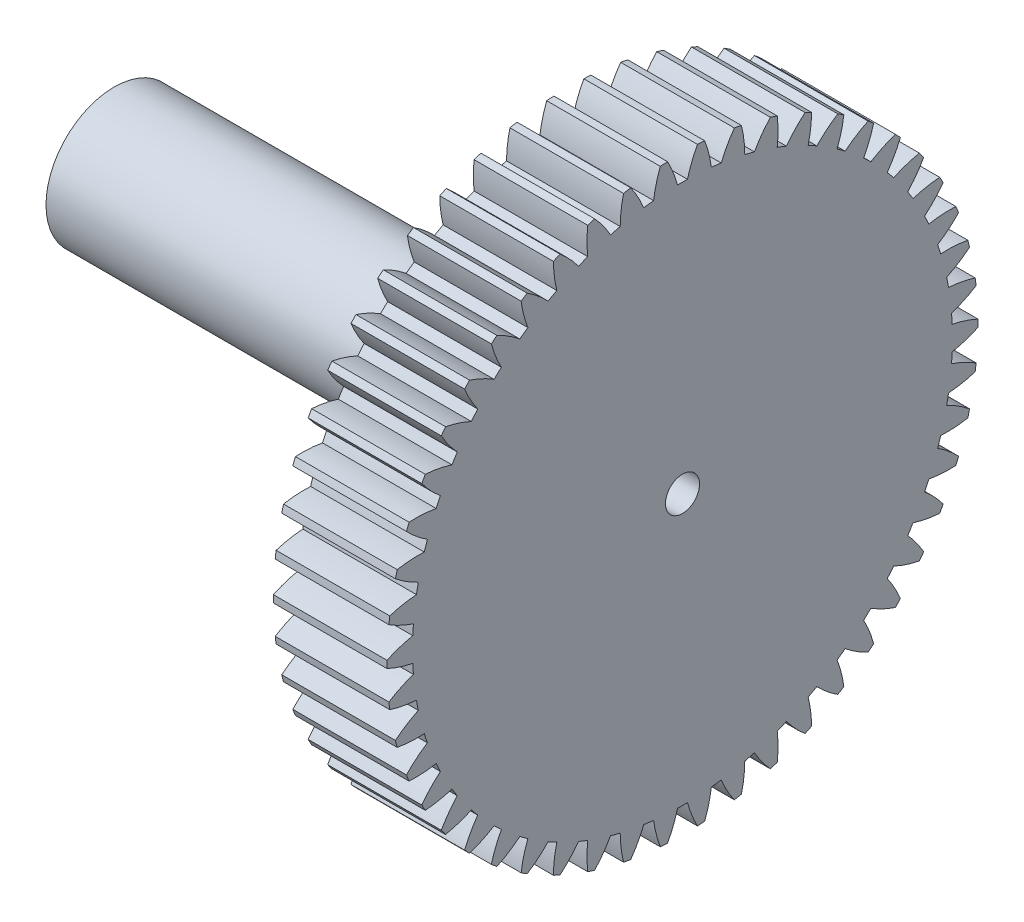
SolidWorks part; units mm, degrees
ref_plane "Plane1" through (0, 0, 0) normal (0, 0, 1) x (1, 0, 0)
ref_plane "Plane2" through (0, 0, 0) normal (0, 1, 0) x (1, 0, 0)
ref_plane "Plane3" through (0, 0, 0) normal (1, 0, 0) x (0, 0, -1)
sketch "HoldingSke" plane through (0, 0, 0) normal (0, 1, 0) x (1, 0, 0)
  line L0 (0, 0) -> (0.6428, -0.766)
  line L1 (-15, 0) -> (100, 0) construction
  line L2 (0, 0) -> (-2.1039, 2.3779)
  line L3 (0, 0) -> (-11.863, 4.5341)
  line L4 (0, 0) -> (5.5511, 6.6156)
  line L5 (0, 0) -> (-46.8476, -17.4728)
  line L6 (0, 0) -> (-8.2896, -5.593)
  line L7 (-2.1039, 2.3779) -> (8.6586, 51.2059)
  line L8 (-76.2, 54.61) -> (-75.7, 54.61)
  line L9 (-71.009, 38.7566) -> (-53.1078, 45.2721)
  line L10 (-76.2, 71.12) -> (104.1128, 71.12)
  line L11 (0, 0) -> (-10, 0)
  line L12 (-76.2, 101.6) -> (-76.162, 101.6)
  line L13 (24.9733, 27.94) -> (52.9518, 28.4284)
  line L14 (24.9733, 27.94) -> (24.9743, 27.94)
  line L15 (24.9733, 27.94) -> (100.4006, 29.5858)
  line L16 (-63.627, -1) -> (-12.827, -1)
  circle A0 centre (0, 0) radius 1.5
  circle A1 centre (0, 0) radius 6
  circle A2 centre (0, 0) radius 6
  circle A3 centre (0, 0) radius 1.5
  dimension "MHD" = 12
  dimension "Hub_dia" = 12
  dimension "Bore" = 3
  dimension "MBD" = 3
  dimension "Num_teeth" = 50
  dimension "Pitch" = 1
  dimension "Overall_len" = 50
  dimension "Show_teeth" = 50
  dimension "Thickness" = 10
  dimension "OAL" = 50.0001
  dimension "T_dim" = 0.5
  dimension "Ap" = 20
  dimension "H" = 19.05
  dimension "Pitch_radius" = 180.3128
  dimension "Width" = 10
  dimension "Backlash" = 0.038
  dimension "Addendum_fac" = 1
  dimension "Dedendum_fac" = 1.25
  dimension "Clearance_fac" = 0.25
  dimension "Dedendum_add" = 0.001
  dimension "Module" = 1
sketch "BasProSke" plane through (0, 0, 0) normal (0, 1, 0) x (1, 0, 0)
  line L0 (-10, 0) -> (60, 0) construction
  line L1 (0, 0) -> (0, 26)
  line L2 (0, 0) -> (10, 0)
  line L3 (10, 0) -> (10, 26)
  line L4 (10, 26) -> (0, 26)
  dimension "Thickness" = 10
  dimension "Diameter" = 52
revolve "Base-Revolve" add sketch "BasProSke" angle 360 about L0
sketch "TooCutSke" plane through (0, 0, 0) normal (1, 0, 0) x (0, 0, -1)
  line L1 (0, 0) -> (0, 107) construction
  line L2 (0, 0) -> (-0.8518, 24.9855) construction
  line L3 (0, 0) -> (-3.1382, 49.8807) construction
  line L4 (-0.8518, 24.9855) -> (-1.5691, 24.9404) construction
  arc A0 (0.4377, 23.745) -> (-0.4377, 23.745) centre (0, 0) ccw
  arc A1 (1.3294, 25.9914) -> (-1.3294, 25.9914) centre (0, 0) ccw
  circle A2 centre (0, 0) radius 25 construction
  circle A3 centre (0, 0) radius 23.4923 construction
  arc A4 (-0.4377, 23.745) -> (-1.3294, 25.9914) centre (-10.1099, 21.2056) ccw
  arc A5 (1.3294, 25.9914) -> (0.4377, 23.745) centre (10.1099, 21.2056) ccw
  dimension "Root_dia" = 47.498
  dimension "Overcut_dia" = 52.0508
  dimension "Pitch_dia" = 50
  dimension "Base_dia" = 46.9846
  dimension "Flank_rad" = 10
  dimension "Half_ang" = 3.6
  dimension "Half_CT" = 0.7188
extrude "ToothCut" cut sketch "TooCutSke" along normal through all
fillet "Breaks" [suppressed] radius 0.02
fillet "RootFillets" [suppressed] radius 0.251
pattern_circular "TeethCuts" count 50 every 7.2 about axis through (-10, 0, 0) along (1, 0, 0) of "ToothCut", "RootFillets", "Breaks"
sketch "HubNeaOneSke" plane through (0, 0, 0) normal (-1, 0, 0) x (0, 0, 1)
  circle A0 centre (0, 0) radius 6
  dimension "Diameter" = 12
extrude "HubNearOne" add sketch "HubNeaOneSke" along normal blind 40.0001
sketch "HubNeaBotSke" plane through (0, 0, 0) normal (-1, 0, 0) x (0, 0, 1)
  circle A0 centre (0, 0) radius 6
  dimension "Diameter" = 12
extrude "HubNearBoth" [suppressed] add sketch "HubNeaBotSke" along normal blind 20
ref_plane "FarPln" through (10, 0, 0) normal (1, 0, 0) x (0, 0, -1)
sketch "HubFarSke" plane through (10, 0, 0) normal (1, 0, 0) x (0, 0, -1)
  circle A0 centre (0, 0) radius 6
  dimension "Diameter" = 12
extrude "HubFar" [suppressed] add sketch "HubFarSke" along normal blind 20
sketch "BorSke" plane through (0, 0, 0) normal (1, 0, 0) x (0, 0, -1)
  circle A0 centre (0, 0) radius 1.5
  dimension "Diameter" = 3
extrude "Bore" cut sketch "BorSke" along normal mid plane 100.0001
sketch "KeySke" plane through (0, 0, 0) normal (1, 0, 0) x (0, 0, -1)
  line L0 (-0.6, 0) -> (-0.6, 2)
  line L1 (-0.6, 2) -> (0.6, 2)
  line L2 (0.6, 2) -> (0.6, 0)
  line L3 (0, 0) -> (0, 34) construction
  line L4 (-0.6, 0) -> (0.6, 0)
  dimension "Offset" = 2
  dimension "Width" = 1.2
extrude "Keyway" [suppressed] cut sketch "KeySke" along normal mid plane 100.0001
pattern_circular "Keyway2" [suppressed] count 2 every 90 about axis through (-10, 0, 0) along (1, 0, 0)
equation "' \"Module@HoldingSke\" = 6.35"
equation "' \"Num_teeth@HoldingSke\" = 12"
equation "' \"Ap@HoldingSke\" =  20"
equation "' \"Ap@HoldingSke\" = 20"
equation "' \"Width@HoldingSke\" = 0.5 * 25.4"
equation "' \"Hub_dia@HoldingSke\"= 1 * 25.4"
equation "' \"Hub_dia@HoldingSke\" = 1 * 25.4"
equation "' \"Overall_len@HoldingSke\" = 1.0 * 25.4"
equation "' \"Bore@HoldingSke\" = 0.75 * 25.4"
equation "' \"T_dim@HoldingSke\" = 0.1 * 25.4"
equation "' \"Width@KeySke\" = 0.25 * 25.4"
equation "' \"Show_teeth@HoldingSke\" = 13"
equation "' \"Backlash@HoldingSke\" = 0.009 * 25.4"
equation "' \"Addendum_fac@HoldingSke\" = 1.0"
equation "' \"Dedendum_fac@HoldingSke\" = 1.25"
equation "' \"Dedendum_add@HoldingSke\" = 0.00005 * 25.4"
equation "' \"Clearance_fac@HoldingSke\" = 0.25"
equation "\"Pitch@HoldingSke\" = 1 / \"Module@HoldingSke\""
equation "\"Overcut_dia@TooCutSke\" = (\"Num_teeth@HoldingSke\" + 2 * \"Addendum_fac@HoldingSke\") / \"Pitch@HoldingSke\" + 0.002 * 25.4"
equation "\"Pitch_dia@TooCutSke\" = \"Num_teeth@HoldingSke\" / \"Pitch@HoldingSke\""
equation "\"Base_dia@TooCutSke\" = \"Num_teeth@HoldingSke\" / \"Pitch@HoldingSke\" * cos((\"Ap@HoldingSke\"  * 3.14159265 / 180))"
equation "\"Root_dia@TooCutSke\" = (\"Num_teeth@HoldingSke\" + 2) / \"Pitch@HoldingSke\" - 2 * (\"Addendum_fac@HoldingSke\" + \"Dedendum_fac@HoldingSke\") / \"Pitch@HoldingSke\" - \"Dedendum_add@HoldingSke\" * 2"
equation "\"Half_ang@TooCutSke\" = 180 / \"Num_teeth@HoldingSke\""
equation "\"Half_CT@TooCutSke\" = \"Num_teeth@HoldingSke\" / \"Pitch@HoldingSke\" * sin((3.14159265 / 2 / \"Num_teeth@HoldingSke\")) / 2 - 7 * \"Backlash@HoldingSke\" / 4"
equation "\"Flank_rad@TooCutSke\" = \"Num_teeth@HoldingSke\" / \"Pitch@HoldingSke\" / 5"
equation "\"Radius@RootFillets\" = \"Clearance_fac@HoldingSke\" / \"Pitch@HoldingSke\" + \"Dedendum_add@HoldingSke\""
equation "\"Break_rad@Breaks\" = 0.02 / \"Pitch@HoldingSke\""
equation "\"Thickness@HoldingSke\" = \"Width@HoldingSke\""
equation "\"OAL@HoldingSke\" = \"Thickness@HoldingSke\""
equation "\"MHD@HoldingSke\" = (\"Num_teeth@HoldingSke\" + 2) / \"Pitch@HoldingSke\" - 2 * (\"Addendum_fac@HoldingSke\" + \"Dedendum_fac@HoldingSke\")  / \"Pitch@HoldingSke\" - \"Dedendum_add@HoldingSke\" * 2"
equation "\"MBD@HoldingSke\" = (\"Num_teeth@HoldingSke\" + 2) / \"Pitch@HoldingSke\" - 2 * (\"Addendum_fac@HoldingSke\" + \"Dedendum_fac@HoldingSke\")  / \"Pitch@HoldingSke\" - \"Dedendum_add@HoldingSke\" * 2 - 0.002 * 25.4"
equation "\"MHD@HoldingSke\" = ((sgn( \"MHD@HoldingSke\" - \"Hub_dia@HoldingSke\" )-1)*( \"MHD@HoldingSke\" - \"Hub_dia@HoldingSke\" ))/-2+ \"Hub_dia@HoldingSke\""
equation "\"MBD@HoldingSke\" = ((sgn( \"MBD@HoldingSke\" - \"Bore@HoldingSke\" )-1)*( \"MBD@HoldingSke\" - \"Bore@HoldingSke\" ))/-2+ \"Bore@HoldingSke\""
equation "\"OAL@HoldingSke\" = ((sgn( \"OAL@HoldingSke\" - \"Overall_len@HoldingSke\" )+1)*( \"OAL@HoldingSke\" - \"Overall_len@HoldingSke\" ))/2 + \"Overall_len@HoldingSke\" + 0.000002 * 25.4"
equation "\"Num_teeth@TeethCuts\" = int( \"Show_teeth@HoldingSke\" ) + 1"
equation "\"Num_teeth@TeethCuts\" = ((sgn( \"Num_teeth@TeethCuts\" - \"Num_teeth@HoldingSke\" )-1)*( \"Num_teeth@TeethCuts\" - \"Num_teeth@HoldingSke\" ))/-2+ \"Num_teeth@HoldingSke\""
equation "\"Num_teeth@TeethCuts\" = ((sgn( \"Num_teeth@TeethCuts\" - 2.0)+1)*( \"Num_teeth@TeethCuts\" - 2.0))/2 +2.0"
equation "\"Angle@TeethCuts\" = 360.0 / \"Num_teeth@HoldingSke\""
equation "\"Diameter@BasProSke\" = (\"Num_teeth@HoldingSke\" + 2 * \"Addendum_fac@HoldingSke\") / \"Pitch@HoldingSke\""
equation "\"Thickness@BasProSke\"  = \"Thickness@HoldingSke\""
equation "' \"Fillet_rad@BasProSke\" =  \"Thickness@HoldingSke\" * 0.05"
equation "' \"Fillet_rad@BasProSke\" = \"Thickness@HoldingSke\" * 0.05"
equation "\"MHD@HoldingSke\" = ((sgn( \"MHD@HoldingSke\" - \"Root_dia@TooCutSke\" )-1)*( \"MHD@HoldingSke\" - \"Root_dia@TooCutSke\" ))/-2+ \"Root_dia@TooCutSke\""
equation "\"Diameter@HubNeaOneSke\" = \"MHD@HoldingSke\""
equation "\"Length@HubNearOne\" = \"OAL@HoldingSke\" - \"Thickness@BasProSke\""
equation "\"Diameter@HubNeaBotSke\" = \"MHD@HoldingSke\""
equation "\"Length@HubNearBoth\" = ( \"OAL@HoldingSke\" - \"Thickness@BasProSke\" ) / 2.0"
equation "\"Thickness@FarPln\" = \"Thickness@BasProSke\""
equation "\"Diameter@HubFarSke\" = \"MHD@HoldingSke\""
equation "\"Length@HubFar\" = ( \"OAL@HoldingSke\" - \"Thickness@BasProSke\" ) / 2.0"
equation "\"Diameter@BorSke\" = \"MBD@HoldingSke\""
equation "\"D1@Bore\" = \"OAL@HoldingSke\" * 2.0"
equation "\"D1@Keyway\" = \"OAL@HoldingSke\" * 2.0"
equation "\"Offset@KeySke\" = \"T_dim@HoldingSke\" + \"MBD@HoldingSke\" / 2.0"
